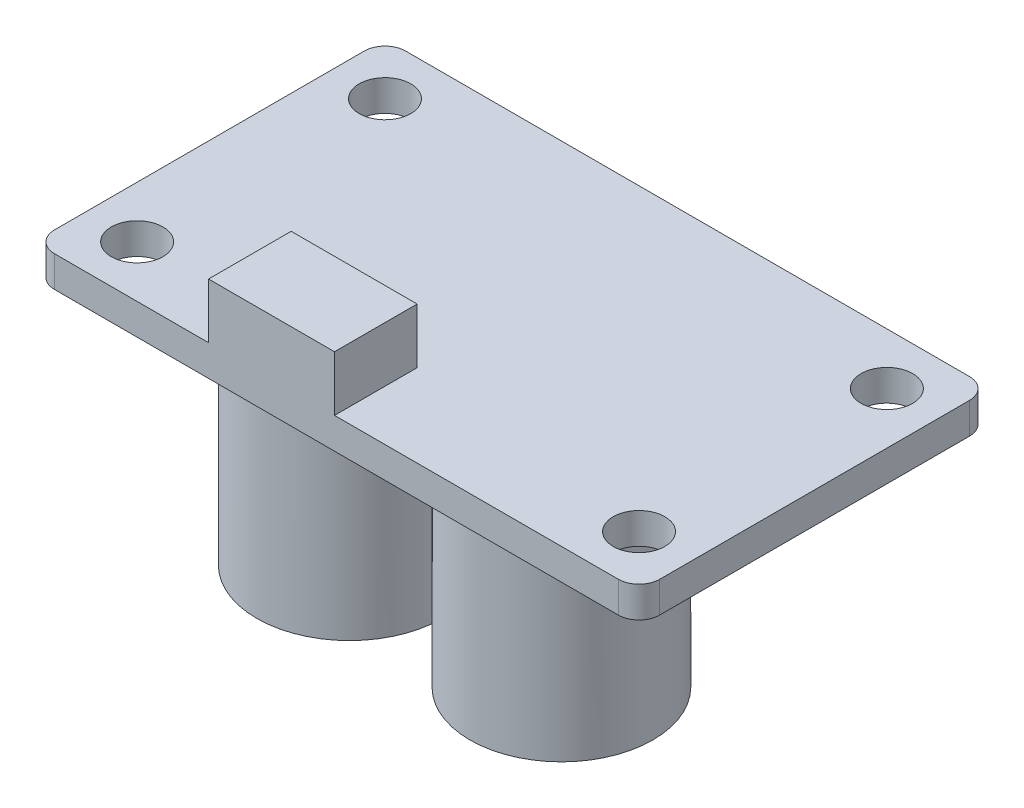
SolidWorks part; units mm, degrees
ref_plane "前视基准面" through (0, 0, 0) normal (0, 0, 1) x (1, 0, 0)
ref_plane "上视基准面" through (0, 0, 0) normal (0, 1, 0) x (1, 0, 0)
ref_plane "右视基准面" through (0, 0, 0) normal (1, 0, 0) x (0, 0, -1)
sketch "草图1" plane through (0, 0, 0) normal (0, 1, 0) x (1, 0, 0)
  line L1 (-14.65, 8.5) -> (14.65, 8.5)
  line L2 (-14.65, 8.5) -> (-14.65, -8.5)
  line L3 (-14.65, -8.5) -> (14.65, -8.5)
  line L4 (14.65, 8.5) -> (14.65, -8.5)
  line L5 (0, -8.5) -> (0, 8.5) construction
  line L6 (-14.65, 0) -> (14.65, 0) construction
  point P0 (0, 0)
  dimension "D1" = 29.3
  dimension "D2" = 17
extrude "凸台-拉伸1" add sketch "草图1" along normal blind 1.5
sketch "草图2" plane through (0, 1.5, 0) normal (0, 1, 0) x (1, 0, 0)
  line L0 (0, 11.303) -> (0, -11.7761) construction
  line L1 (-19.5042, 0) -> (17.8745, 0) construction
  circle A0 centre (-12.15, 6) radius 1.25
  circle A1 centre (12.15, 6) radius 1.25
  circle A2 centre (12.15, -6) radius 1.25
  circle A3 centre (-12.15, -6) radius 1.25
  dimension "D1" = 2.5
  dimension "D2" = 24.3
  dimension "D3" = 12
extrude "切除-拉伸1" cut sketch "草图2" against normal through all
sketch "草图4" plane through (0, 0, 8.5) normal (0, 0, 1) x (1, 0, 0)
  line L0 (86.0036, 138.4155) -> (488.6703, 138.4155) construction
  line L1 (-14.65, 1.5) -> (14.65, 1.5) construction
  line L2 (-6.1914, 1.5) -> (-0.0929, 1.5)
  line L3 (-6.1914, 1.5) -> (-6.1914, 4.1701)
  line L4 (-6.1914, 4.1701) -> (-0.0929, 4.1701)
  line L5 (-0.0929, 1.5) -> (-0.0929, 4.1701)
  point P8 (-6.1914, 4.1701)
extrude "凸台-拉伸2" add sketch "草图4" against normal blind 4
sketch "草图5" plane through (0, 0, 0) normal (0, -1, 0) x (1, 0, 0)
  line L0 (38.2219, 85.4857) -> (249.5552, 85.4857) construction
  circle A0 centre (-4.9618, 2.9039) radius 4.4923
  circle A1 centre (5.296, 2.9039) radius 4.4293
extrude "凸台-拉伸3" add sketch "草图5" along normal blind 10
sketch "草图6" plane through (0, 0, 0) normal (0, -1, 0) x (1, 0, 0)
  circle A0 centre (0, -5.4403) radius 2.7469
extrude "凸台-拉伸4" add sketch "草图6" along normal blind 2
fillet "圆角1" radius 1 4 edges at (14.65, 0.75, -8.5) (-14.65, 0.75, -8.5) (-14.65, 0.75, 8.5) (14.65, 0.75, 8.5)
equation "\"m\"= 2"
